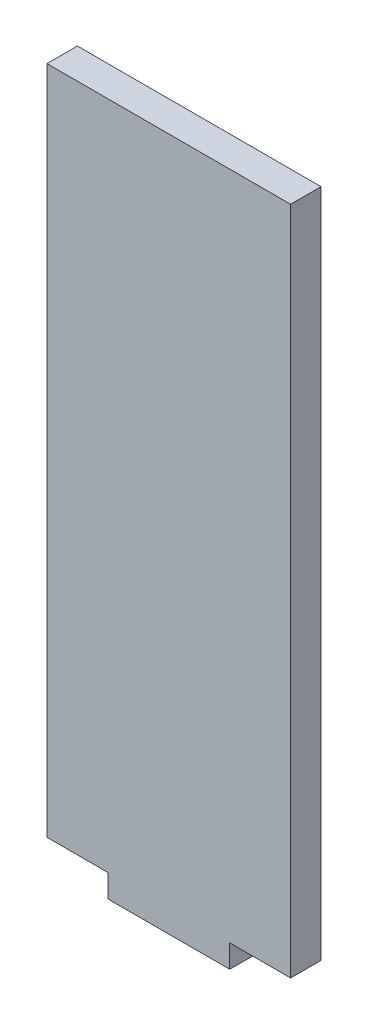
SolidWorks part; units mm, degrees
ref_plane "Front Plane" through (0, 0, 0) normal (0, 0, 1) x (1, 0, 0)
ref_plane "Top Plane" through (0, 0, 0) normal (0, 1, 0) x (1, 0, 0)
ref_plane "Right Plane" through (0, 0, 0) normal (1, 0, 0) x (0, 0, -1)
sketch "Sketch1" plane through (0, 0, 0) normal (0, 0, 1) x (1, 0, 0)
  line L0 (6.35, 0) -> (6.35, -2.3879)
  line L1 (0, 0) -> (6.35, 0)
  line L2 (0, 0) -> (0, 69.85)
  line L3 (0, 69.85) -> (25.4, 69.85)
  line L4 (25.4, 0) -> (25.4, 69.85)
  line L5 (6.35, -2.3879) -> (19.05, -2.3879)
  line L6 (19.05, -2.3879) -> (19.05, 0)
  line L7 (12.7, -2.3879) -> (12.7, 0) construction
  line L8 (19.05, 0) -> (25.4, 0)
  dimension "D1" = 25.4
  dimension "D2" = 69.85
  dimension "D3" = 12.7
extrude "Boss-Extrude1" add sketch "Sketch1" along normal blind 3.175
